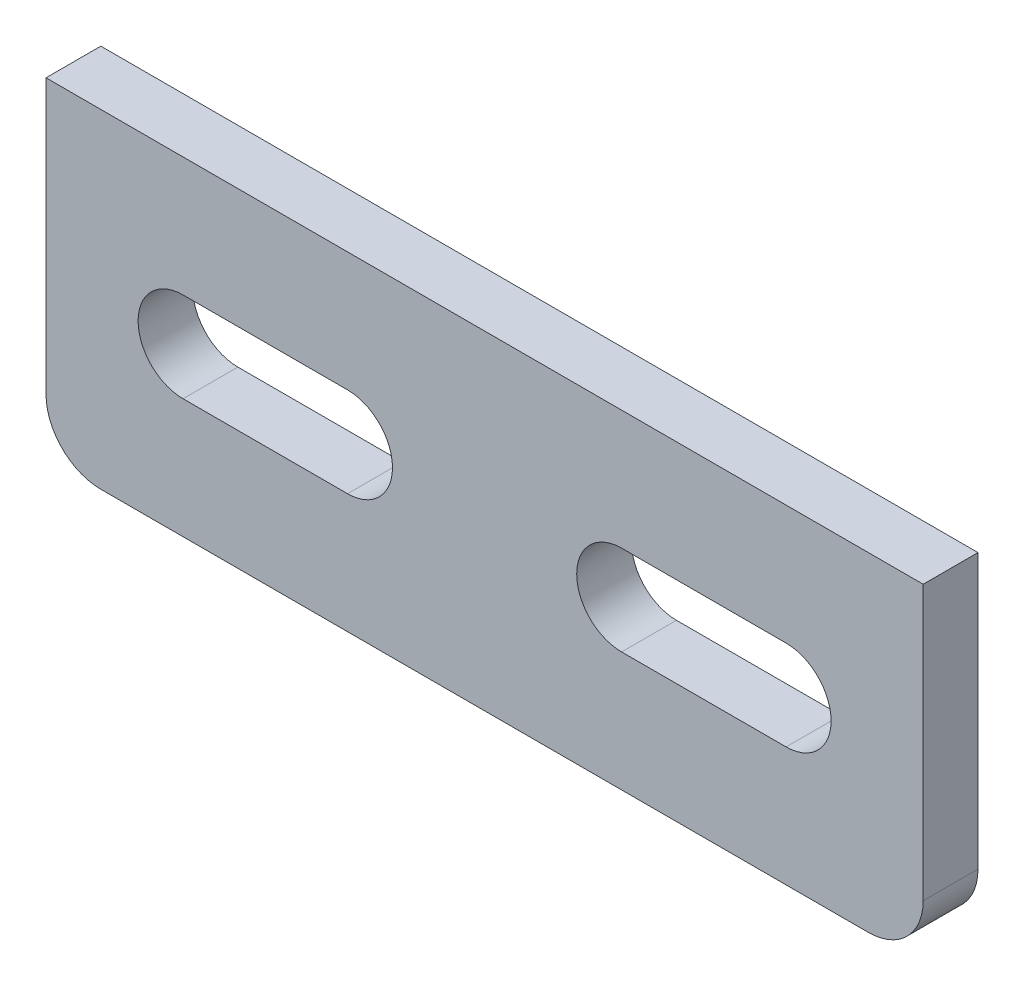
SolidWorks part; units mm, degrees
ref_plane "Ön Düzlem" through (0, 0, 0) normal (0, 0, 1) x (1, 0, 0)
ref_plane "Üst Düzlem" through (0, 0, 0) normal (0, 1, 0) x (1, 0, 0)
ref_plane "Sağ Düzlem" through (0, 0, 0) normal (1, 0, 0) x (0, 0, -1)
sketch "Çizim1" plane through (0, 0, 0) normal (0, 0, 1) x (1, 0, 0)
  line L1 (-40, 15) -> (40, 15)
  line L2 (-40, 15) -> (-40, -15)
  line L3 (-40, -15) -> (40, -15)
  line L4 (40, 15) -> (40, -15)
  line L5 (-40, 15) -> (40, -15) construction
  line L6 (-40, -15) -> (40, 15) construction
  point P0 (0, 0)
  dimension "D1" = 80
  dimension "D2" = 30
extrude "Yükseklik-Ekstrüzyon1" add sketch "Çizim1" along normal blind 5
fillet "Radyus2" radius 5 2 edges at (40, -15, 2.5) (-40, -15, 2.5)
sketch "Çizim2" plane through (0, 0, 5) normal (0, 0, 1) x (1, 0, 0)
  line L0 (-27.5, 0) -> (-12.5, 0) construction
  line L1 (-27.5, 4.1) -> (-12.5, 4.1)
  line L2 (-27.5, -4.1) -> (-12.5, -4.1)
  line L3 (12.5, 0) -> (27.5, 0) construction
  line L4 (12.5, 4.1) -> (27.5, 4.1)
  line L5 (12.5, -4.1) -> (27.5, -4.1)
  arc A2 (-27.5, 4.1) -> (-27.5, -4.1) centre (-27.5, 0) ccw
  arc A3 (-12.5, -4.1) -> (-12.5, 4.1) centre (-12.5, 0) ccw
  arc A4 (12.5, 4.1) -> (12.5, -4.1) centre (12.5, 0) ccw
  arc A5 (27.5, -4.1) -> (27.5, 4.1) centre (27.5, 0) ccw
  point P4 (-20, 0)
  point P10 (20, 0)
  dimension "D1" = 4.1
  dimension "D2" = 4.1
  dimension "D3" = 15
  dimension "D6" = 20
  dimension "D4" = 15
  dimension "D5" = 20
extrude "Kes-Ekstrüzyon1" cut sketch "Çizim2" against normal blind 8
